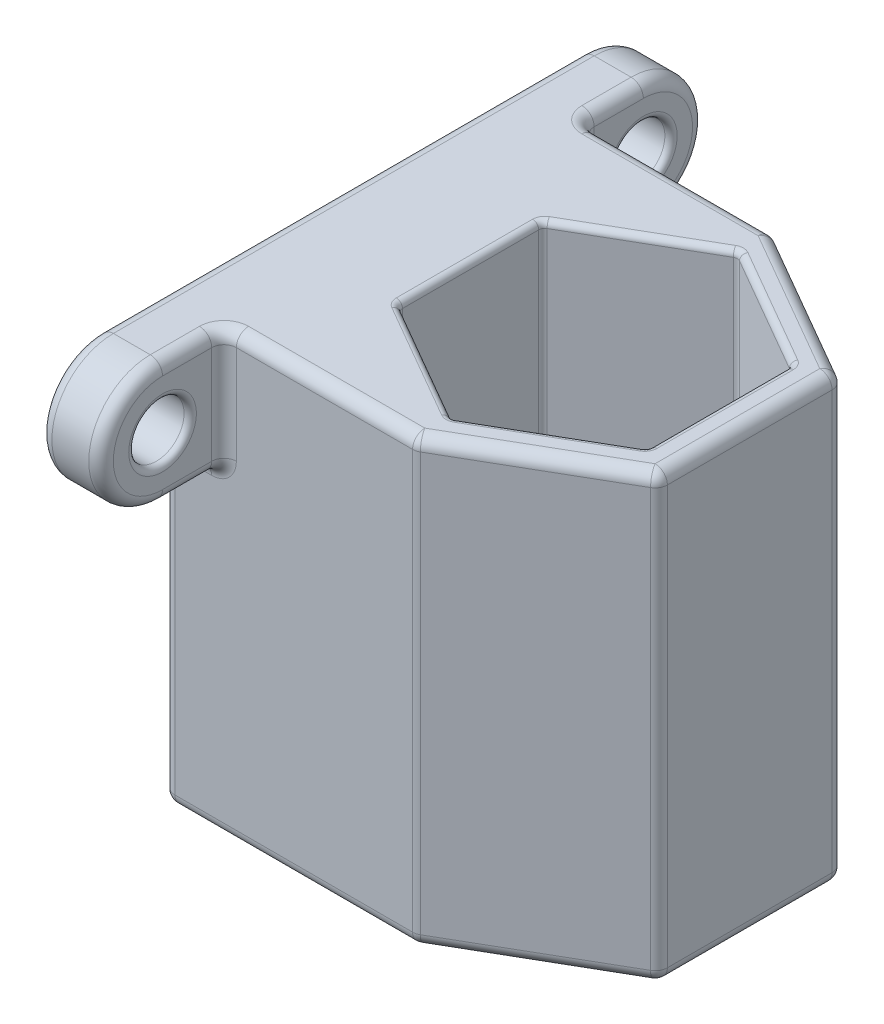
SolidWorks part; units mm, degrees
ref_plane "Front Plane" through (0, 0, 0) normal (0, 0, 1) x (1, 0, 0)
ref_plane "Top Plane" through (0, 0, 0) normal (0, 1, 0) x (1, 0, 0)
ref_plane "Right Plane" through (0, 0, 0) normal (1, 0, 0) x (0, 0, -1)
sketch "Sketch1" plane through (0, 0, 0) normal (0, 1, 0) x (1, 0, 0)
  line L0 (0, -11.6625) -> (0, 0) construction
  line L5 (0, -11.6625) -> (10.1, -5.8312)
  line L6 (10.1, -5.8312) -> (10.1, 5.8312)
  line L7 (10.1, 5.8312) -> (0, 11.6625)
  line L8 (0, 11.6625) -> (-10.1, 5.8312)
  line L9 (-10.1, 5.8312) -> (-10.1, -5.8312)
  line L10 (-10.1, -5.8312) -> (0, -11.6625)
  line L11 (0, -14.5492) -> (0, -11.6625) construction
  line L12 (12.6, -7.2746) -> (12.6, 7.2746)
  line L13 (12.6, 7.2746) -> (0, 14.5492)
  line L14 (0, 14.5492) -> (-12.6, 7.2746)
  line L15 (-12.6, 7.2746) -> (-12.6, -7.2746)
  line L16 (-12.6, -7.2746) -> (0, -14.5492)
  line L17 (0, -14.5492) -> (12.6, -7.2746)
  circle A0 centre (0, 0) radius 10.1 construction
  circle A1 centre (0, 0) radius 12.6 construction
  dimension "D1" = 20.2
  dimension "D2" = 2.5
extrude "Boss-Extrude1" add sketch "Sketch1" along normal blind 25
sketch "Sketch2" plane through (0, 0, 0) normal (0, -1, 0) x (1, 0, 0)
  line L1 (0, -14.5492) -> (12.6, -7.2746)
  line L2 (12.6, -7.2746) -> (12.6, 7.2746)
  line L3 (12.6, 7.2746) -> (0, 14.5492)
  line L4 (0, 14.5492) -> (-12.6, 7.2746)
  line L5 (-12.6, 7.2746) -> (-12.6, -7.2746)
  line L6 (-12.6, -7.2746) -> (0, -14.5492)
  circle A0 centre (0, 0) radius 12.6 construction
extrude "Boss-Extrude2" add sketch "Sketch2" along normal blind 2.5
sketch "Sketch3" plane through (0, -2.5, 0) normal (0, -1, 0) x (1, 0, 0)
  line L0 (0, 0) -> (0, -4.6188) construction
  line L1 (0, -4.6188) -> (4, -2.3094)
  line L2 (4, -2.3094) -> (4, 2.3094)
  line L3 (4, 2.3094) -> (0, 4.6188)
  line L4 (0, 4.6188) -> (-4, 2.3094)
  line L5 (-4, 2.3094) -> (-4, -2.3094)
  line L6 (-4, -2.3094) -> (0, -4.6188)
  line L7 (0, -14.5492) -> (12.6, -7.2746)
  line L8 (12.6, -7.2746) -> (12.6, 7.2746)
  line L9 (12.6, 7.2746) -> (0, 14.5492)
  line L10 (0, 14.5492) -> (-12.6, 7.2746)
  line L11 (-12.6, 7.2746) -> (-12.6, -7.2746)
  line L12 (-12.6, -7.2746) -> (0, -14.5492)
  circle A0 centre (0, 0) radius 4 construction
  circle A1 centre (0, 0) radius 12.6 construction
  dimension "D1" = 8
extrude "Boss-Extrude3" add sketch "Sketch3" along normal blind 6
sketch "Sketch4" plane through (0, -8.5, 0) normal (0, -1, 0) x (1, 0, 0)
  line L1 (0, -14.5492) -> (12.6, -7.2746)
  line L2 (12.6, -7.2746) -> (12.6, 7.2746)
  line L3 (12.6, 7.2746) -> (0, 14.5492)
  line L4 (0, 14.5492) -> (-12.6, 7.2746)
  line L5 (-12.6, 7.2746) -> (-12.6, -7.2746)
  line L6 (-12.6, -7.2746) -> (0, -14.5492)
  circle A0 centre (0, 0) radius 12.6 construction
extrude "Boss-Extrude4" add sketch "Sketch4" along normal blind 2.5
sketch "Sketch5" plane through (0, -11, 0) normal (0, -1, 0) x (1, 0, 0)
  circle A0 centre (0, 0) radius 2.625
  dimension "D1" = 5.25
extrude "Cut-Extrude1" cut sketch "Sketch5" against normal through all
sketch "Sketch6" plane through (0, -11, 0) normal (0, -1, 0) x (1, 0, 0)
  line L0 (0, 14.5492) -> (-20.6, 14.5492)
  line L1 (-20.6, 14.5492) -> (-20.6, -14.5492)
  line L2 (-20.6, -14.5492) -> (0, -14.5492)
  line L3 (0, 14.5492) -> (-12.6, 7.2746)
  line L4 (-12.6, 7.2746) -> (-12.6, -7.2746)
  line L5 (-12.6, -7.2746) -> (0, -14.5492)
  dimension "D1" = 8
extrude "Boss-Extrude5" add sketch "Sketch6" against normal up to surface (36 mm away) up to face at (0, 25, 0)
sketch "Sketch7" plane through (-20.6, 0, 0) normal (-1, 0, 0) x (0, 0, 1)
  line L0 (-19.5492, 25) -> (19.5492, 25)
  line L1 (-19.5492, 15) -> (19.5492, 15)
  line L2 (0, 0) -> (0, 15) construction
  line L3 (14.5492, 25) -> (-14.5492, 25) construction
  line L4 (-14.5492, 25) -> (-14.5492, -11) construction
  circle A0 centre (-19.5492, 20) radius 5
  circle A1 centre (19.5492, 20) radius 5
  circle A2 centre (19.5492, 20) radius 2.25
  circle A3 centre (-19.5492, 20) radius 2.25
  line M8 (14.5492, -11) -> (14.5492, 25)
  line M10 (-14.5492, 25) -> (-14.5492, -11)
  dimension "D1" = 4.5
  dimension "D2" = 2.75
extrude "Boss-Extrude6" add sketch "Sketch7" against normal blind 5 contours A0 L0 M10 | A0 L1 M10 | A0 A3 | A1 A2 | A1 L1 M8 | A1 L0 M8
sketch "Sketch8" plane through (0, -2.5, 0) normal (0, -1, 0) x (1, 0, 0)
  circle A0 centre (0, 0) radius 2.625
  circle A1 centre (0, 0) radius 2.625 construction
extrude "Boss-Extrude7" add sketch "Sketch8" against normal blind 0.2
fillet "Fillet1" radius 0.5 19 edges at (0, 0, -2.625) (10.1, 25, 0) (10.1, 0, 0) (5.05, 25, -8.7469) (10.1, 12.5, -5.8312) (5.05, 0, -8.7469) (10.1, 12.5, 5.8312) (5.05, 25, 8.7469) (5.05, 0, 8.7469) (0, 12.5, 11.6625) (-5.05, 25, 8.7469) (-5.05, 0, 8.7469) (-10.1, 12.5, 5.8312) (-10.1, 25, 0) (-10.1, 0, 0) (-10.1, 12.5, -5.8312) (-5.05, 25, -8.7469) (0, 12.5, -11.6625) (-5.05, 0, -8.7469)
fillet "Fillet2" radius 1 32 edges at (-15.6, 15, 17.0492) (-15.6, 25, 17.0492) (-15.6, 25, -17.0492) (-15.6, 15, -17.0492) (-20.6, 15, 17.0492) (-20.6, 15, -17.0492) (-20.6, 20, -24.5492) (-15.6, 20, -24.5492) (-20.6, 2, -14.5492) (-10.3, -11, -14.5492) (-7.8, 25, -14.5492) (-15.6, 20, -14.5492) (-18.1, 15, -14.5492) (6.3, 25, -10.9119) (0, 7, -14.5492) (6.3, -11, -10.9119) (-7.8, 25, 14.5492) (-10.3, -11, 14.5492) (-20.6, 2, 14.5492) (-18.1, 15, 14.5492) (-15.6, 20, 14.5492) (12.6, 25, 0) (12.6, 7, -7.2746) (12.6, -11, 0) (6.3, 25, 10.9119) (12.6, 7, 7.2746) (6.3, -11, 10.9119) (0, 7, 14.5492) (-15.6, 20, 24.5492) (-20.6, 20, 24.5492) (-20.6, -11, 0) (-20.6, 25, 0)
fillet "Fillet3" radius 0.5 6 edges at (-20.6, 20, -17.2992) (-15.6, 20, -17.2992) (-20.6, 20, 21.7992) (-15.6, 20, 21.7992) (0, -8.5, -2.625) (0, -11, -2.625)
